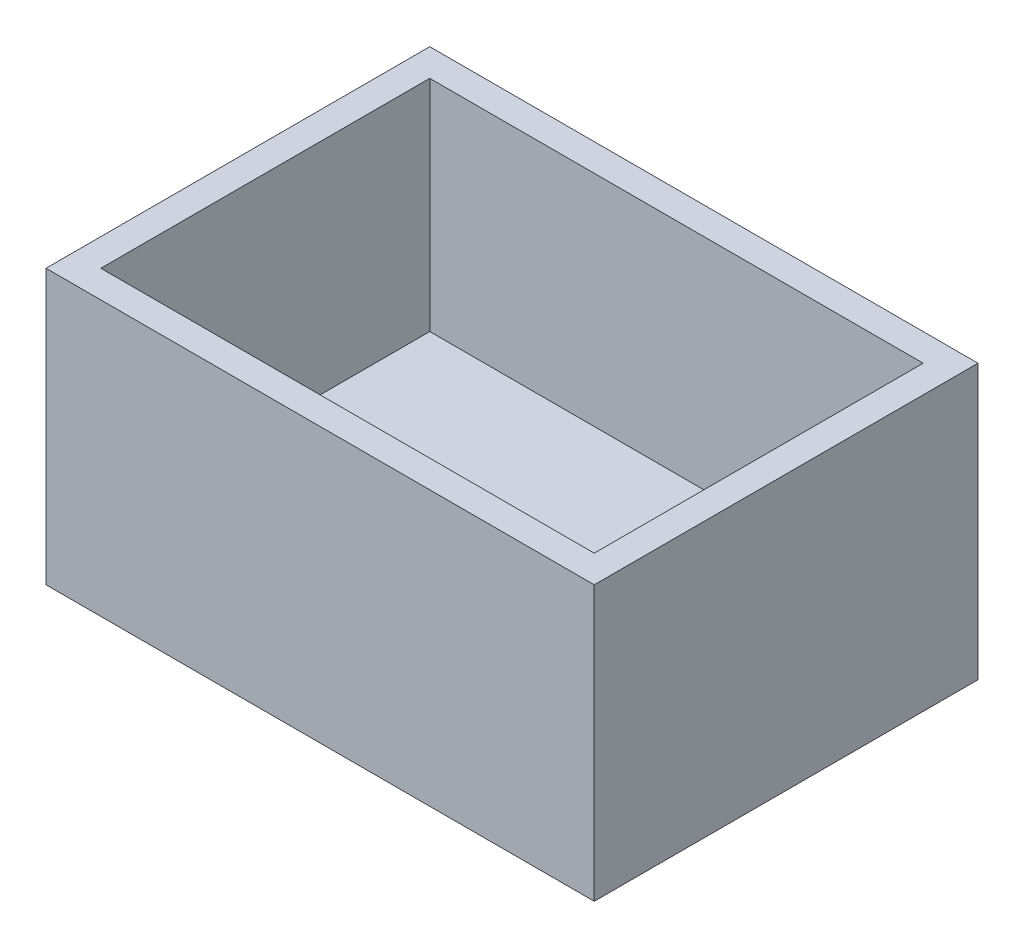
SolidWorks part; units mm, degrees
ref_plane "Front Plane" through (0, 0, 0) normal (0, 0, 1) x (1, 0, 0)
ref_plane "Top Plane" through (0, 0, 0) normal (0, 1, 0) x (1, 0, 0)
ref_plane "Right Plane" through (0, 0, 0) normal (1, 0, 0) x (0, 0, -1)
sketch "Sketch1" plane through (0, 0, 0) normal (0, 1, 0) x (1, 0, 0)
  line L1 (-127, -88.9) -> (127, -88.9)
  line L2 (-127, -88.9) -> (-127, 88.9)
  line L3 (-127, 88.9) -> (127, 88.9)
  line L4 (127, -88.9) -> (127, 88.9)
  line L5 (-127, -88.9) -> (127, 88.9) construction
  line L6 (-127, 88.9) -> (127, -88.9) construction
  point P0 (0, 0)
  dimension "D1" = 254
  dimension "D2" = 177.8
extrude "Boss-Extrude1" add sketch "Sketch1" along normal blind 127
sketch "Sketch2" plane through (0, 127, 0) normal (0, 1, 0) x (1, 0, 0)
  line L1 (-114.3, -76.2) -> (114.3, -76.2)
  line L2 (-114.3, -76.2) -> (-114.3, 76.2)
  line L3 (-114.3, 76.2) -> (114.3, 76.2)
  line L4 (114.3, -76.2) -> (114.3, 76.2)
  line L5 (-114.3, -76.2) -> (114.3, 76.2) construction
  line L6 (-114.3, 76.2) -> (114.3, -76.2) construction
  point P0 (0, 0)
  dimension "D1" = 152.4
  dimension "D2" = 228.6
extrude "Cut-Extrude1" cut sketch "Sketch2" against normal blind 101.6
